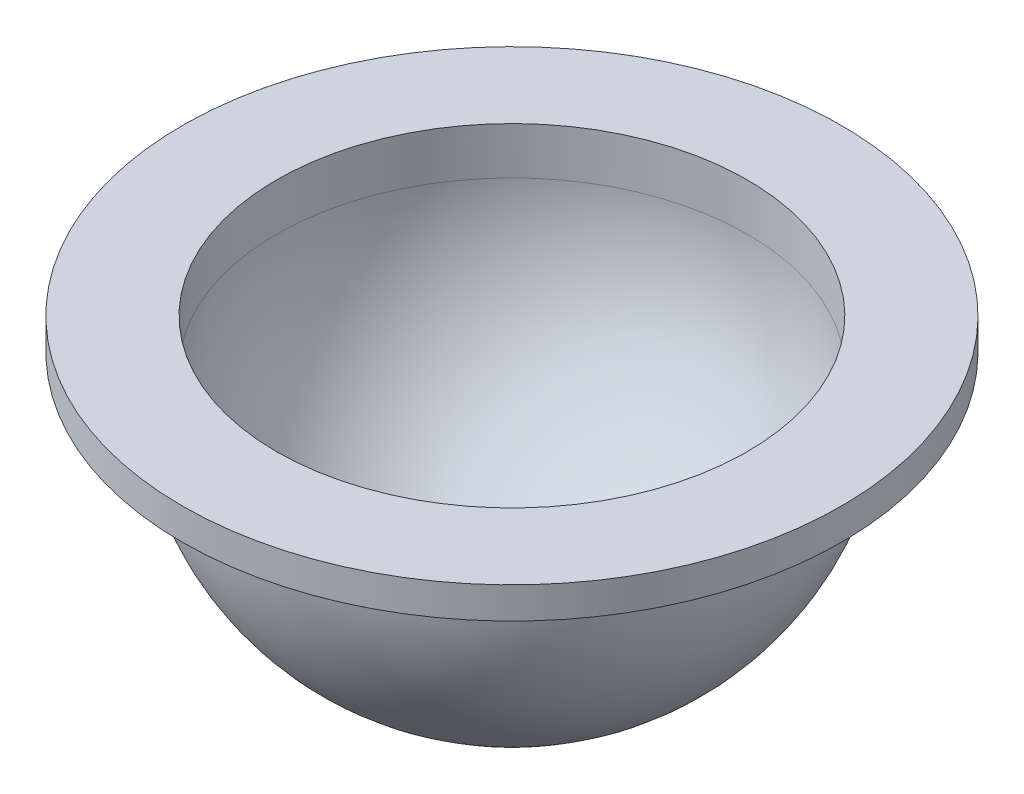
SolidWorks part; units mm, degrees
ref_plane "Front Plane" through (0, 0, 0) normal (0, 0, 1) x (1, 0, 0)
ref_plane "Top Plane" through (0, 0, 0) normal (0, 1, 0) x (1, 0, 0)
ref_plane "Right Plane" through (0, 0, 0) normal (1, 0, 0) x (0, 0, -1)
sketch "Sketch1" plane through (0, 0, 0) normal (1, 0, 0) x (0, 0, -1)
  line L0 (0, 0) -> (0, -2)
  line L1 (0, -2) -> (4, -2)
  line L2 (21, -18) -> (21, -20)
  line L3 (6, -3) -> (6, 0)
  line L4 (6, 0) -> (0, 0)
  line L5 (21, 28.1303) -> (21, -56.0633) construction
  line L6 (4, -3) -> (4, -2)
  arc A0 (4, -3) -> (21, -20) centre (21, -3) ccw
  arc A1 (21, -18) -> (6, -3) centre (21, -3) cw
  point P4 (0, 0)
  point P13 (0, 0)
  point P14 (0, 0)
  point P15 (0, 0)
  point P16 (33.272, -3.5198)
  point P17 (21, -12.9278)
  dimension "D1" = 15
  dimension "D2" = 2
  dimension "D3" = 2
  dimension "D4" = 20
  dimension "D6" = 4
revolve "Revolve1" add sketch "Sketch1" angle 360 about L5
